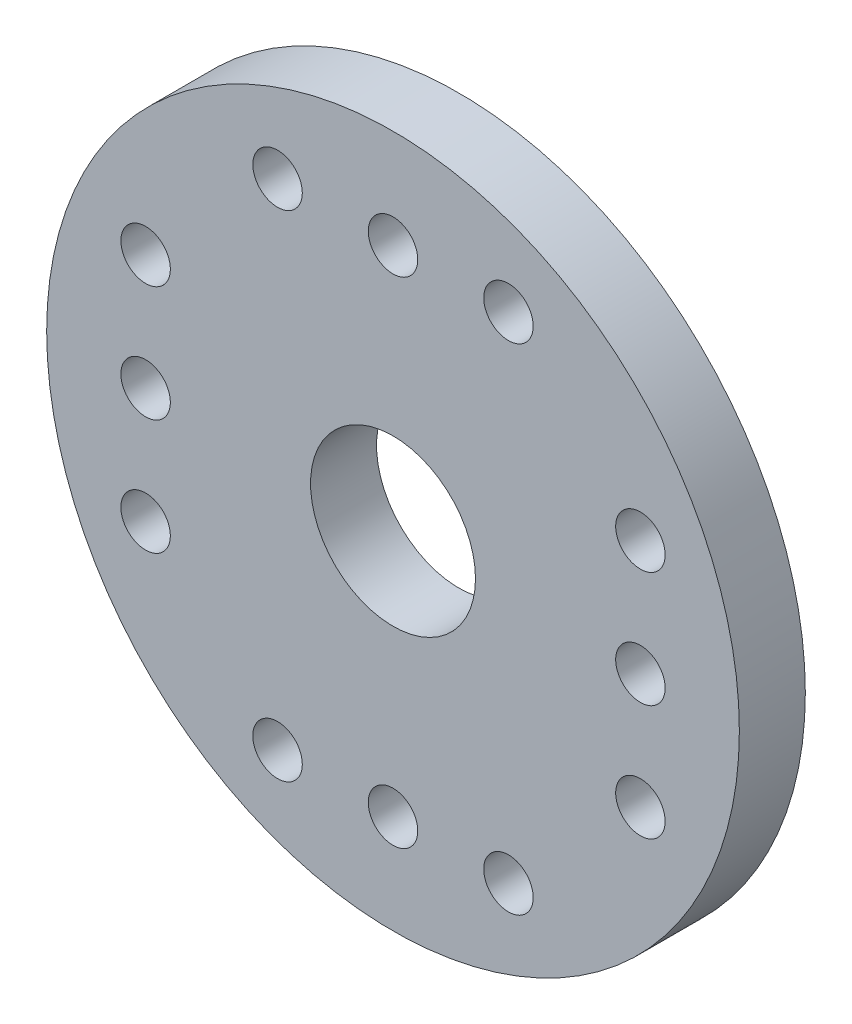
SolidWorks part; units mm, degrees
ref_plane "Alzado" through (0, 0, 0) normal (0, 0, 1) x (1, 0, 0)
ref_plane "Planta" through (0, 0, 0) normal (0, 1, 0) x (1, 0, 0)
ref_plane "Vista lateral" through (0, 0, 0) normal (1, 0, 0) x (0, 0, -1)
sketch "Croquis1" plane through (0, 0, 0) normal (0, 0, 1) x (1, 0, 0)
  line L0 (-12.452, 7.5) -> (13.473, 7.5) construction
  line L1 (0, 0) -> (0, 11.2228) construction
  circle A0 centre (0, 0) radius 10.5
  circle A1 centre (0, 7.5) radius 0.75
  circle A2 centre (-3.5, 7.5) radius 0.75
  circle A3 centre (3.5, 7.5) radius 0.75
  circle A4 centre (7.5, 3.5) radius 0.75
  circle A5 centre (7.5, 0) radius 0.75
  circle A6 centre (7.5, -3.5) radius 0.75
  circle A7 centre (3.5, -7.5) radius 0.75
  circle A8 centre (0, -7.5) radius 0.75
  circle A9 centre (-3.5, -7.5) radius 0.75
  circle A10 centre (-7.5, -3.5) radius 0.75
  circle A11 centre (-7.5, 0) radius 0.75
  circle A12 centre (-7.5, 3.5) radius 0.75
  circle A13 centre (0, 0) radius 2.5
  point P33 (0, 0)
  dimension "D1" = 21
  dimension "D3" = 1.5
  dimension "D7" = 5
  dimension "D2" = 7.5
  dimension "D4" = 3.5
  dimension "D5" = 3.5
  dimension "D6" = 4
extrude "Saliente-Extruir1" add sketch "Croquis1" along normal blind 2
